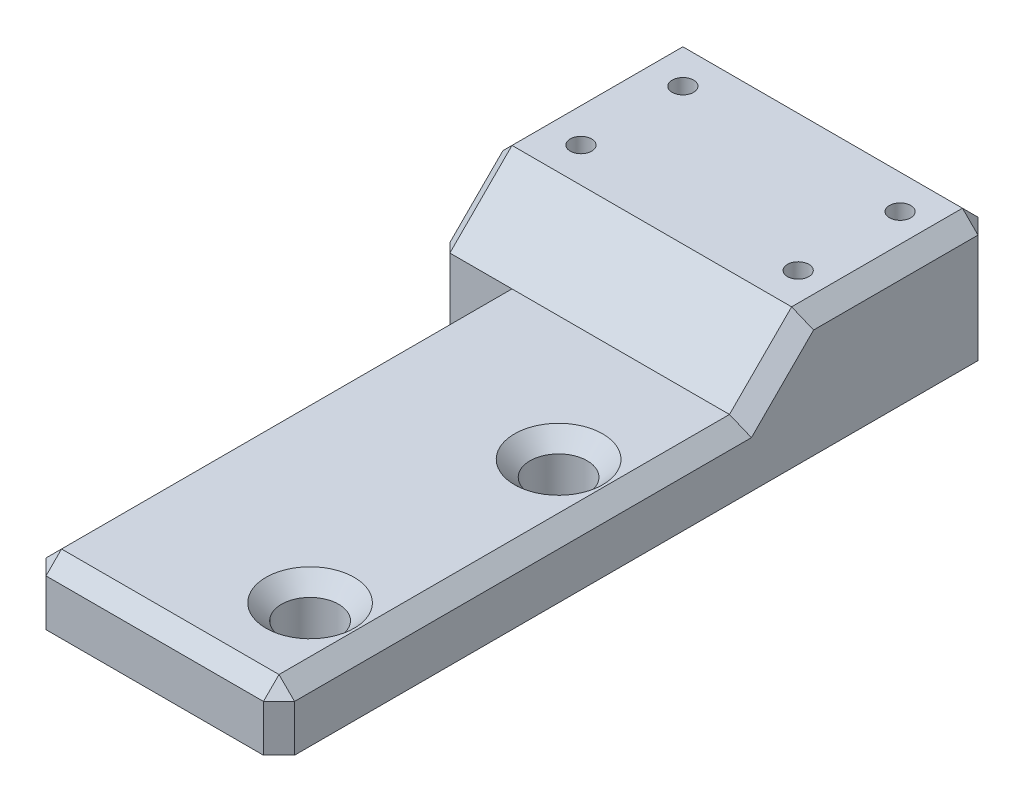
SolidWorks part; units mm, degrees
ref_plane "Front Plane" through (0, 0, 0) normal (0, 0, 1) x (1, 0, 0)
ref_plane "Top Plane" through (0, 0, 0) normal (0, 1, 0) x (1, 0, 0)
ref_plane "Right Plane" through (0, 0, 0) normal (1, 0, 0) x (0, 0, -1)
sketch "Sketch1" plane through (0, 0, 0) normal (0, 1, 0) x (1, 0, 0)
  line L1 (0, 0) -> (31.75, 0)
  line L2 (0, 0) -> (0, 73.025)
  line L3 (0, 73.025) -> (31.75, 73.025)
  line L4 (31.75, 0) -> (31.75, 73.025)
  circle A0 centre (25.4, 9.525) radius 2.921
  circle A1 centre (25.4, 34.925) radius 2.921
  dimension "D3" = 5.842
  dimension "D1" = 31.75
  dimension "D2" = 6.35
  dimension "0.375" = 9.525
  dimension "D4" = 25.4
  dimension "D5" = 38.1
extrude "Boss-Extrude1" add sketch "Sketch1" along normal blind 12.7
sketch "Sketch2" plane through (31.75, 0, 0) normal (1, 0, 0) x (0, 0, -1)
  line L0 (73.025, 12.7) -> (73.025, 0) construction
  line L1 (0, 12.7) -> (47.625, 12.7)
  line L2 (0, 12.7) -> (0, 6.35)
  line L3 (0, 6.35) -> (47.625, 6.35)
  line L4 (47.625, 12.7) -> (47.625, 6.35)
  dimension "D1" = 25.4
  dimension "D2" = 6.35
extrude "Cut-Extrude1" cut sketch "Sketch2" against normal through all
sketch "Sketch3" plane through (0, 0, 0) normal (0, -1, 0) x (1, 0, 0)
  line L0 (0, -73.025) -> (0, 0) construction
  line L2 (31.75, -73.025) -> (0, -73.025) construction
  line L3 (0, 0) -> (6.35, 0)
  line L4 (0, 0) -> (0, -47.625)
  line L5 (0, -47.625) -> (6.35, -47.625)
  line L6 (6.35, 0) -> (6.35, -47.625)
  circle A0 centre (27.2796, -57.531) radius 1.0922
  circle A1 centre (5.08, -67.945) radius 1.0922
  circle A2 centre (27.2796, -67.945) radius 1.0922
  circle A3 centre (5.08, -57.531) radius 1.0922
  dimension "D1" = 2.1844
  dimension "D2" = 22.1996
  dimension "D3" = 5.08
  dimension "D4" = 5.08
  dimension "D5" = 6.35
  dimension "D6" = 10.414
  dimension "2.625" = 47.625
extrude "Cut-Extrude2" cut sketch "Sketch3" against normal through all
chamfer "Chamfer1" distance 6.35 angle 45 1 edges at (15.875, 12.7, -47.625)
chamfer "Chamfer2" distance 1.5875 angle 45 15 edges at (25.4, 6.35, -12.446) (25.4, 6.35, -37.846) (31.75, 6.35, -73.025) (31.75, 3.175, 0) (6.35, 3.175, 0) (6.35, 6.35, -23.8125) (19.05, 6.35, 0) (31.75, 6.35, -23.8125) (31.75, 9.525, -50.8) (31.75, 12.7, -63.5) (0, 6.35, -73.025) (15.875, 12.7, -73.025) (0, 12.7, -63.5) (0, 9.525, -50.8) (0, 3.175, -47.625)
